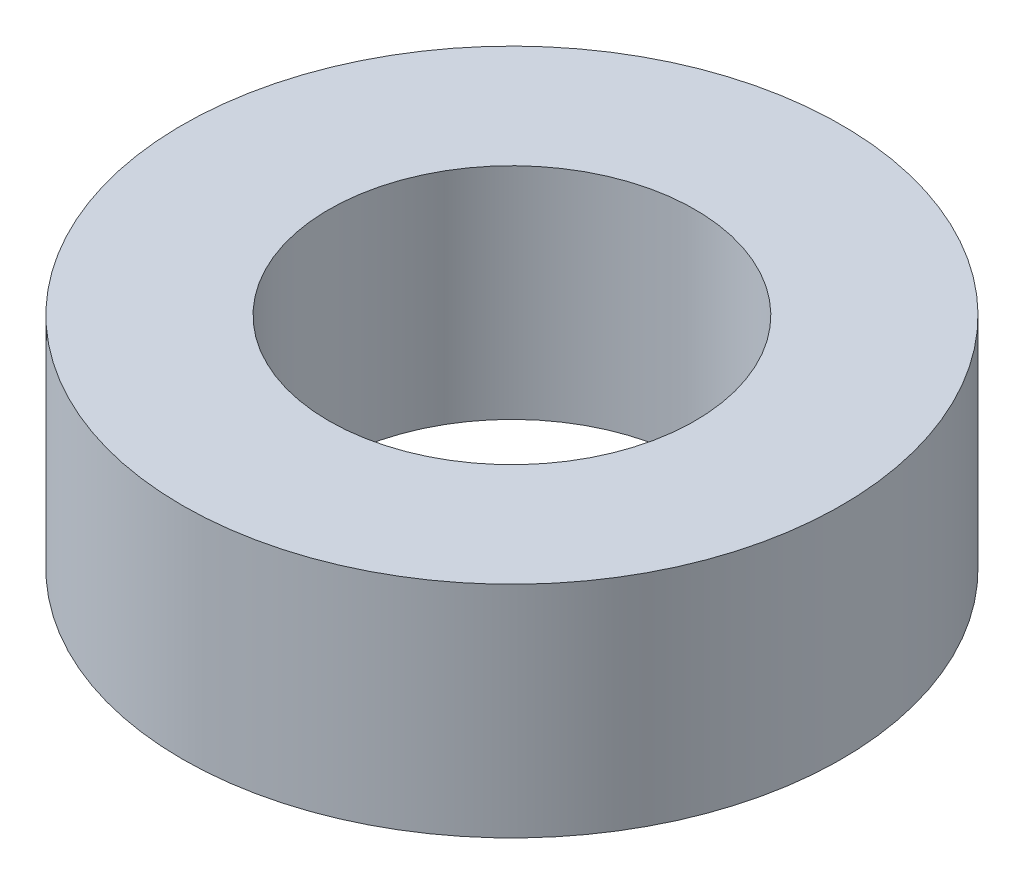
SolidWorks part; units mm, degrees
ref_plane "Front Plane" through (0, 0, 0) normal (0, 0, 1) x (1, 0, 0)
ref_plane "Top Plane" through (0, 0, 0) normal (0, 1, 0) x (1, 0, 0)
ref_plane "Right Plane" through (0, 0, 0) normal (1, 0, 0) x (0, 0, -1)
sketch "Sketch1" plane through (0, 0, 0) normal (0, 1, 0) x (1, 0, 0)
  circle A0 centre (0, 0) radius 9
  circle A1 centre (0, 0) radius 5
extrude "Boss-Extrude1" add sketch "Sketch1" along normal mid plane 6
